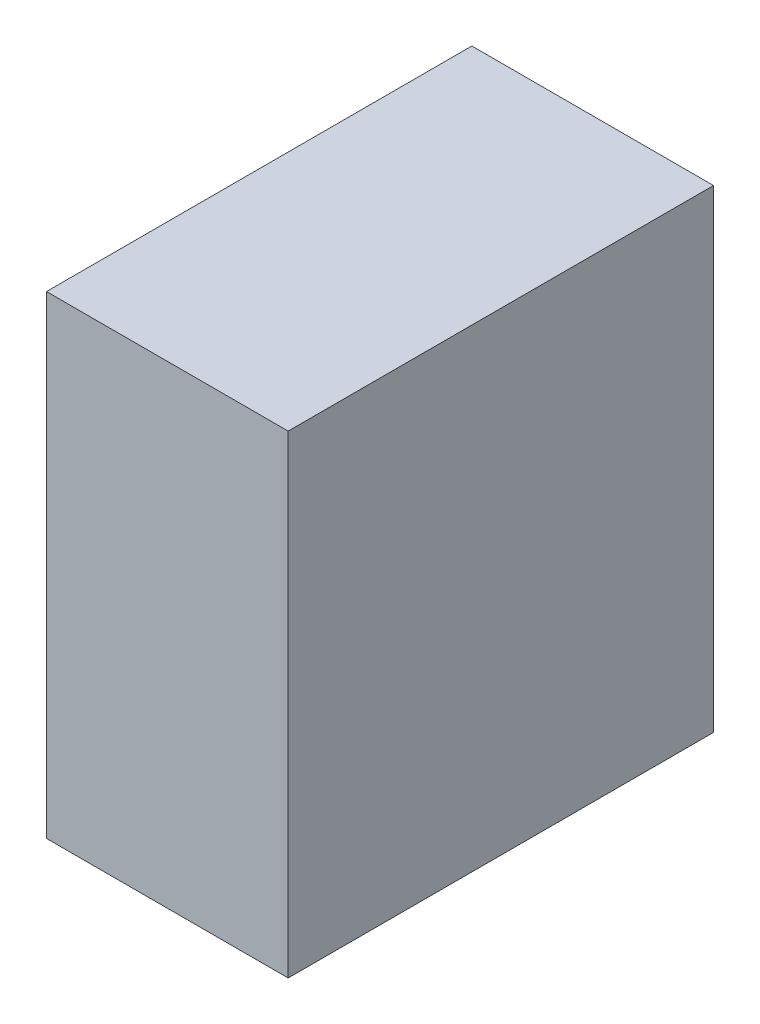
SolidWorks part; units mm, degrees
ref_plane "Front Plane" through (0, 0, 0) normal (0, 0, 1) x (1, 0, 0)
ref_plane "Top Plane" through (0, 0, 0) normal (0, 1, 0) x (1, 0, 0)
ref_plane "Right Plane" through (0, 0, 0) normal (1, 0, 0) x (0, 0, -1)
sketch "Sketch1" plane through (0, 0, 0) normal (1, 0, 0) x (0, 0, -1)
  line L1 (-110, -122.5) -> (110, -122.5)
  line L2 (-110, -122.5) -> (-110, 122.5)
  line L3 (-110, 122.5) -> (110, 122.5)
  line L4 (110, -122.5) -> (110, 122.5)
  line L5 (-110, -122.5) -> (110, 122.5) construction
  line L6 (-110, 122.5) -> (110, -122.5) construction
  point P0 (0, 0)
extrude "Boss-Extrude1" add sketch "Sketch1" along normal blind 125
